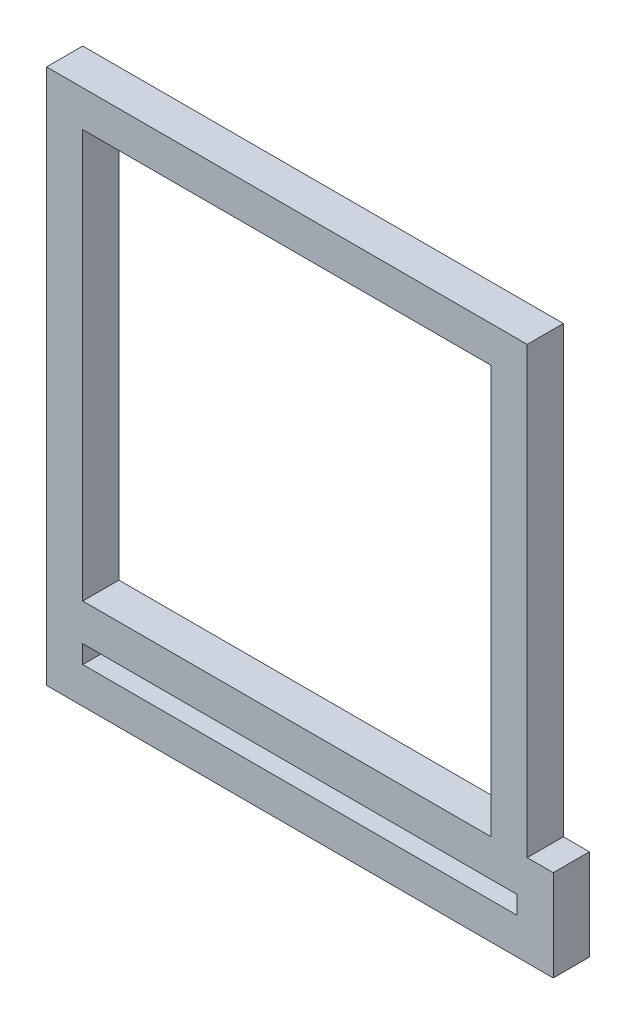
SolidWorks part; units mm, degrees
ref_plane "Спереди" through (0, 0, 0) normal (0, 0, 1) x (1, 0, 0)
ref_plane "Сверху" through (0, 0, 0) normal (0, 1, 0) x (1, 0, 0)
ref_plane "Справа" through (0, 0, 0) normal (1, 0, 0) x (0, 0, -1)
sketch "Эскиз1" plane through (0, 0, 0) normal (0, 0, 1) x (1, 0, 0)
  line L1 (0, 0) -> (70, 0)
  line L2 (0, 0) -> (0, 74)
  line L3 (0, 74) -> (70, 74)
  line L4 (70, 0) -> (70, 74)
  dimension "D1" = 74
  dimension "D2" = 70
extrude "Вытянуть1" add sketch "Эскиз1" along normal blind 5
sketch "Эскиз2" plane through (0, 0, 5) normal (0, 0, 1) x (1, 0, 0)
  line L0 (0, 0) -> (70, 0) construction
  line L1 (5, 7.5) -> (65, 7.5)
  line L2 (5, 7.5) -> (5, 5)
  line L3 (5, 5) -> (65, 5)
  line L4 (65, 7.5) -> (65, 5)
  dimension "D1" = 60
  dimension "D2" = 5
  dimension "D3" = 5
  dimension "D4" = 2.5
extrude "Вытянуть2" cut sketch "Эскиз2" against normal up to next
sketch "Эскиз3" plane through (0, 0, 5) normal (0, 0, 1) x (1, 0, 0)
  line L0 (70, 74) -> (0, 74) construction
  line L1 (5, 69) -> (61.4, 69)
  line L2 (5, 69) -> (5, 12.6)
  line L3 (5, 12.6) -> (61.4, 12.6)
  line L4 (61.4, 69) -> (61.4, 12.6)
  line L5 (0, 74) -> (0, 0) construction
  dimension "D1" = 56.4
  dimension "D2" = 5
  dimension "D3" = 5
extrude "Вытянуть3" cut sketch "Эскиз3" against normal blind 20
sketch "Эскиз4" plane through (0, 0, 0) normal (0, 0, -1) x (-1, 0, 0)
  line L0 (-61.4, 12.6) -> (-5, 12.6) construction
  line L1 (-70, 74) -> (-66.4, 74)
  line L2 (-70, 74) -> (-70, 12.6)
  line L3 (-70, 12.6) -> (-66.4, 12.6)
  line L4 (-66.4, 74) -> (-66.4, 12.6)
  line L5 (-61.4, 69) -> (-61.4, 12.6) construction
  dimension "D1" = 5
extrude "Вытянуть5" cut sketch "Эскиз4" against normal through all
